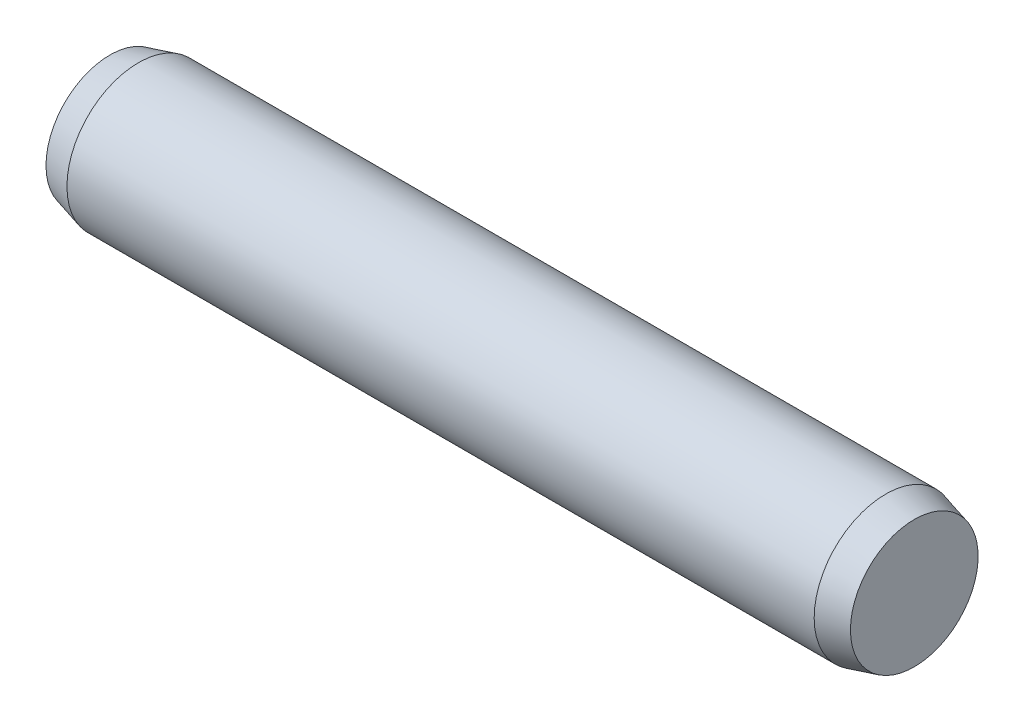
SolidWorks part; units mm, degrees
ref_plane "Plane1" through (0, 0, 0) normal (0, 0, 1) x (1, 0, 0)
ref_plane "Plane2" through (0, 0, 0) normal (0, 1, 0) x (1, 0, 0)
ref_plane "Plane3" through (0, 0, 0) normal (1, 0, 0) x (0, 0, -1)
other "Configuration Table"
sketch "Sketch1" plane through (0, 0, 0) normal (0, 0, 1) x (1, 0, 0)
  line L1 (-6.35, 0) -> (107.95, 0) construction
  line L2 (0, 0) -> (45, 0)
  line L3 (45, 0) -> (45, 3.5713)
  line L4 (45, 3.5713) -> (43.4, 4)
  line L5 (43.4, 4) -> (1.6, 4)
  line L6 (0, 3.5713) -> (0, 0)
  line L7 (0, 3.5713) -> (1.6, 4)
  dimension "Chamfer_len" = 1.6
  dimension "D3" = 15
  dimension "Diameter" = 8
  dimension "D1" = 1.6
  dimension "D2" = 15
revolve "Base-Revolve" add sketch "Sketch1" angle 360 about L1
equation "\"D3@Sketch1\" = 15.0"
equation "\"D1@Sketch1\" = \"Chamfer_len@Sketch1\""
equation "\"D2@Sketch1\" = \"D3@Sketch1\""
